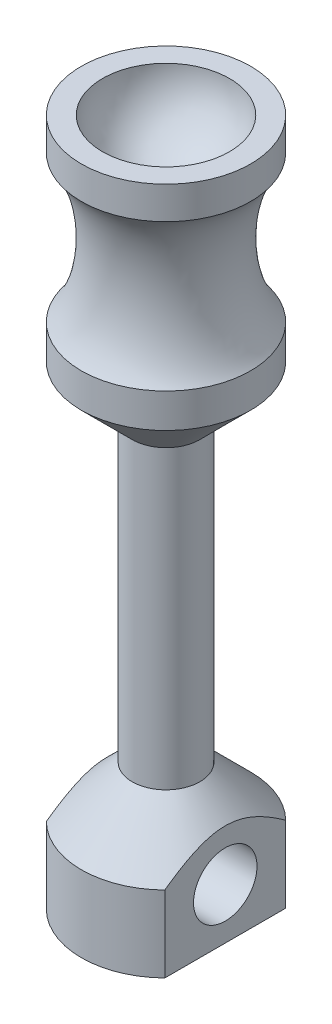
SolidWorks part; units mm, degrees
ref_plane "Front Plane" through (0, 0, 0) normal (0, 0, 1) x (1, 0, 0)
ref_plane "Top Plane" through (0, 0, 0) normal (0, 1, 0) x (1, 0, 0)
ref_plane "Right Plane" through (0, 0, 0) normal (1, 0, 0) x (0, 0, -1)
sketch "Sketch1" plane through (0, 0, 0) normal (0, 1, 0) x (1, 0, 0)
  circle A0 centre (0, 0) radius 6.35
  dimension "D1" = 12.7
extrude "Boss-Extrude1" add sketch "Sketch1" along normal blind 54.102
sketch "Sketch2" plane through (0, 0, 0) normal (0, 0, 1) x (1, 0, 0)
  line L0 (6.35, 54.102) -> (-6.35, 54.102) construction
  line L1 (26.0571, 38.1) -> (6.35, 38.1)
  line L2 (26.0571, 38.1) -> (26.0571, 8.255)
  line L3 (26.0571, 8.255) -> (6.35, 8.255)
  line L4 (2.54, 34.29) -> (2.54, 12.065)
  line L5 (0, 0) -> (0, 54.102) construction
  line L6 (6.35, 38.1) -> (2.54, 34.29)
  line L7 (6.35, 8.255) -> (2.54, 12.065)
  dimension "D4" = 45
  dimension "D1" = 16.002
  dimension "D2" = 29.845
  dimension "D3" = 2.54
  dimension "D5" = 6.35
revolve "Cut-Revolve1" cut sketch "Sketch2" angle 360 about L5
sketch "Sketch3" plane through (0, 0, 0) normal (0, 0, 1) x (1, 0, 0)
  line L0 (-6.35, 0) -> (6.35, 0) construction
  line L1 (10.795, 14.605) -> (4.445, 14.605)
  line L2 (10.795, 14.605) -> (10.795, 0)
  line L3 (10.795, 0) -> (4.445, 0)
  line L4 (4.445, 14.605) -> (4.445, 0)
  line L6 (6.35, 8.255) -> (-6.35, 8.255) construction
  dimension "D1" = 4.445
  dimension "D2" = 6.35
  dimension "D3" = 6.35
extrude "Cut-Extrude1" cut sketch "Sketch3" against normal through all both and the other way through all contours L1 L4 L3 L2
mirror "Mirror1" about plane through (0, 0, 0) normal (1, 0, 0) of "Cut-Extrude1"
hole_wizard "3/16 (0.1875) Diameter Hole1" positions "Sketch5" profile "Sketch6" hole size "3/16" standard "ANSI Inch" end condition through all
sketch "Sketch5" plane through (-4.445, 0, 0) normal (-1, 0, 0) x (0, 0, 1)
  line L0 (-4.5348, 0) -> (4.5348, 0) construction
  point P0 (0, 6.35)
  dimension "D1" = 6.35
sketch "Sketch6" plane through (-4.445, 6.35, 0) normal (0, 1, 0) x (0, 0, 1)
  line L0 (0, 0) -> (0, 10.795)
  line L1 (0, 10.795) -> (2.3812, 10.795)
  line L2 (2.3812, 10.795) -> (2.3812, 0)
  line L5 (2.3812, 0) -> (0, 0)
  line L11 (0, -6.35) -> (0, 107.95) construction
  dimension "Thru Hole Dia." = 4.7625
  dimension "Thru Hole Depth" = 10.795
sketch "Sketch7" plane through (0, 0, 0) normal (0, 0, 1) x (1, 0, 0)
  line L0 (6.35, 54.102) -> (-6.35, 54.102) construction
  line L1 (6.35, 38.1) -> (6.35, 54.102) construction
  line L2 (0, 0) -> (0, 8.6987) construction
  ellipse E0 centre (7.9375, 46.1645) end of major axis (7.9375, 39.8145) minor radius 3.175
  dimension "D1" = 12.7
  dimension "D2" = 6.35
  dimension "D3" = 1.5875
  dimension "D4" = 1.5875
revolve "Cut-Revolve2" cut sketch "Sketch7" angle 360 about L2
sketch "Sketch8" plane through (0, 0, 0) normal (1, 0, 0) x (0, 0, -1)
  line L0 (6.35, 54.102) -> (-6.35, 54.102) construction
  line L1 (4.7625, 54.102) -> (-4.7625, 54.102)
  arc A0 (-4.7625, 54.102) -> (4.7625, 54.102) centre (0, 54.102) ccw
  dimension "D1" = 9.525
revolve "Cut-Revolve3" cut sketch "Sketch8" angle 360 about L1
sketch "Sketch9" plane through (4.445, 0, 0) normal (1, 0, 0) x (0, 0, -1)
  line L1 (-11.2076, 2.54) -> (14.1924, 2.54)
  line L2 (-11.2076, 2.54) -> (-11.2076, -10.16)
  line L3 (-11.2076, -10.16) -> (14.1924, -10.16)
  line L4 (14.1924, 2.54) -> (14.1924, -10.16)
  circle A0 centre (0, 6.35) radius 2.3812 construction
  dimension "D1" = 3.81
  dimension "D2" = 25.4
  dimension "D3" = 12.7
extrude "Cut-Extrude2" cut sketch "Sketch9" against normal through all both and the other way through all
